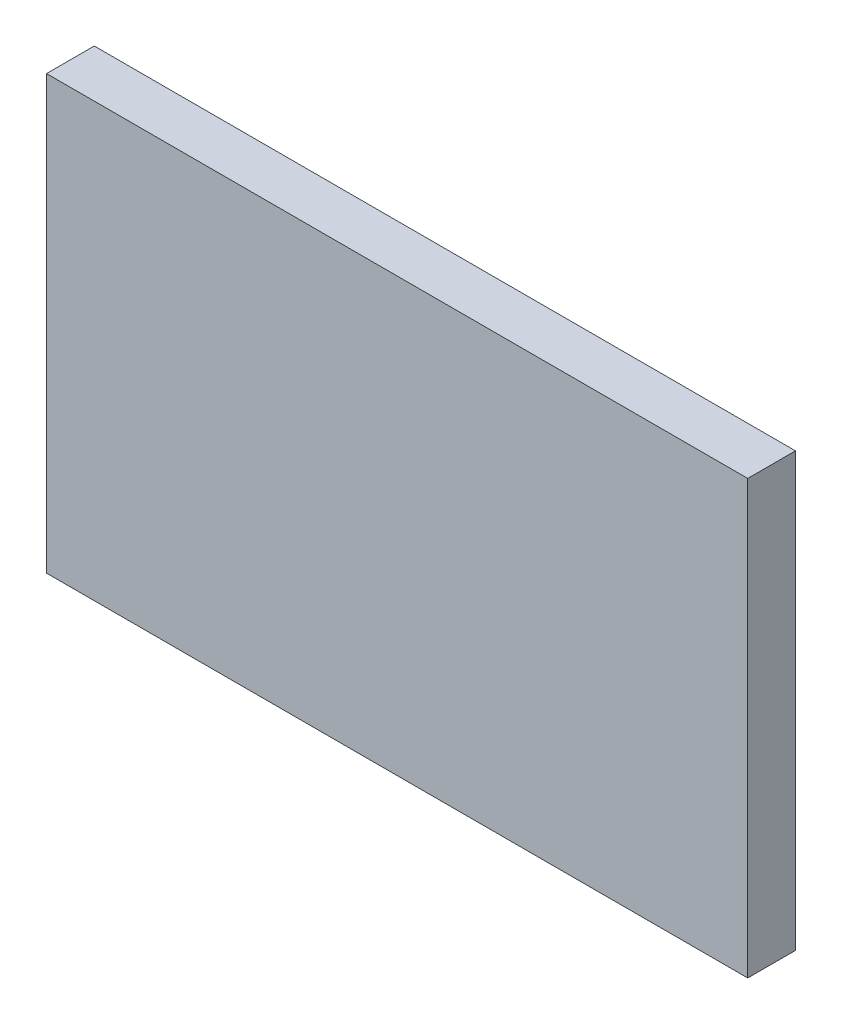
SolidWorks part; units mm, degrees
ref_plane "Front Plane" through (0, 0, 0) normal (0, 0, 1) x (1, 0, 0)
ref_plane "Top Plane" through (0, 0, 0) normal (0, 1, 0) x (1, 0, 0)
ref_plane "Right Plane" through (0, 0, 0) normal (1, 0, 0) x (0, 0, -1)
sketch "Sketch1" plane through (0, 0, 0) normal (0, 0, 1) x (1, 0, 0)
  line L1 (-117.5, 72.5) -> (117.5, 72.5)
  line L2 (-117.5, 72.5) -> (-117.5, -72.5)
  line L3 (-117.5, -72.5) -> (117.5, -72.5)
  line L4 (117.5, 72.5) -> (117.5, -72.5)
  line L5 (-117.5, 72.5) -> (117.5, -72.5) construction
  line L6 (-117.5, -72.5) -> (117.5, 72.5) construction
  point P0 (0, 0)
  dimension "D1" = 235
  dimension "D2" = 145
extrude "Boss-Extrude1" add sketch "Sketch1" along normal blind 16
